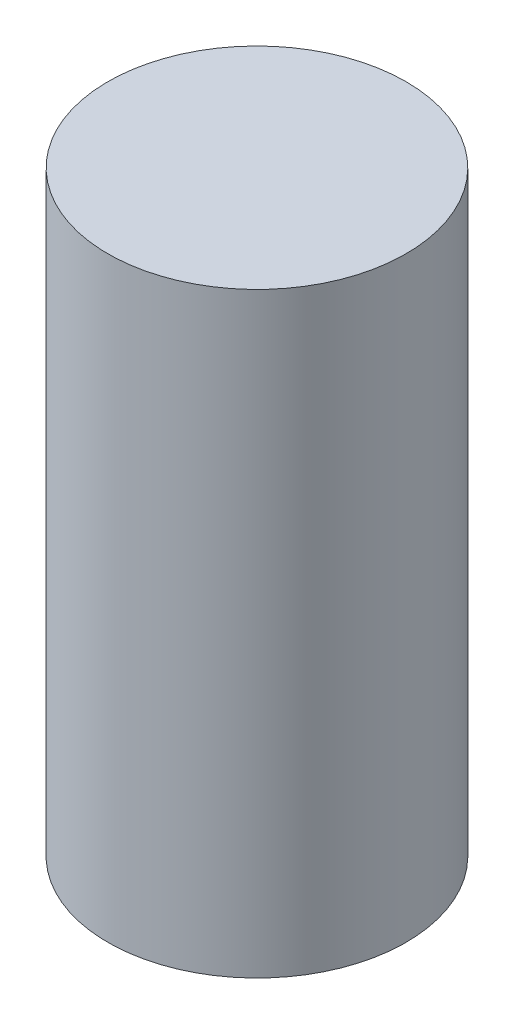
SolidWorks part; units mm, degrees
ref_plane "Front Plane" through (0, 0, 0) normal (0, 0, 1) x (1, 0, 0)
ref_plane "Top Plane" through (0, 0, 0) normal (0, 1, 0) x (1, 0, 0)
ref_plane "Right Plane" through (0, 0, 0) normal (1, 0, 0) x (0, 0, -1)
sketch "Sketch1" plane through (0, 0, 0) normal (0, 1, 0) x (1, 0, 0)
  circle A0 centre (0, 0) radius 14.5
  dimension "D1" = 29
extrude "Boss-Extrude1" add sketch "Sketch1" along normal blind 58
